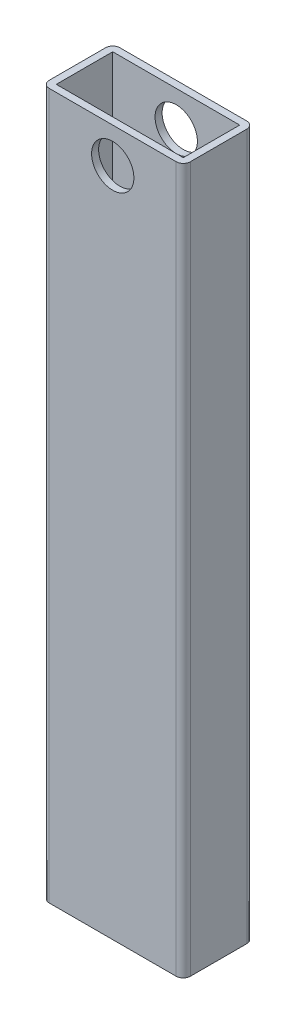
SolidWorks part; units mm, degrees
ref_plane "Piano frontale" through (0, 0, 0) normal (0, 0, 1) x (1, 0, 0)
ref_plane "Piano superiore" through (0, 0, 0) normal (0, 1, 0) x (1, 0, 0)
ref_plane "Piano destro" through (0, 0, 0) normal (1, 0, 0) x (0, 0, -1)
sketch "Schizzo2" plane through (0, 0, 0) normal (0, 1, 0) x (1, 0, 0)
  line L1 (-10, 5) -> (10, 5)
  line L2 (-10, 5) -> (-10, -5)
  line L3 (-10, -5) -> (10, -5)
  line L4 (10, 5) -> (10, -5)
  line L5 (-10, 5) -> (10, -5) construction
  line L6 (-10, -5) -> (10, 5) construction
  point P0 (0, 0)
  dimension "D1" = 20
  dimension "D2" = 10
extrude "Estrusione-Sottile1" add sketch "Schizzo2" against normal blind 100 thin
sketch "Schizzo3" plane through (0, 0, 5) normal (0, 0, 1) x (1, 0, 0)
  line L0 (-10, 0) -> (10, 0) construction
  circle A0 centre (0, -5) radius 3
  dimension "D1" = 6
  dimension "D2" = 5
extrude "Taglio-Estrusione1" cut sketch "Schizzo3" against normal through all
fillet "Raccordo6" radius 1 4 edges at (-10, -50, -5) (10, -50, -5) (-10, -50, 5) (10, -50, 5)
